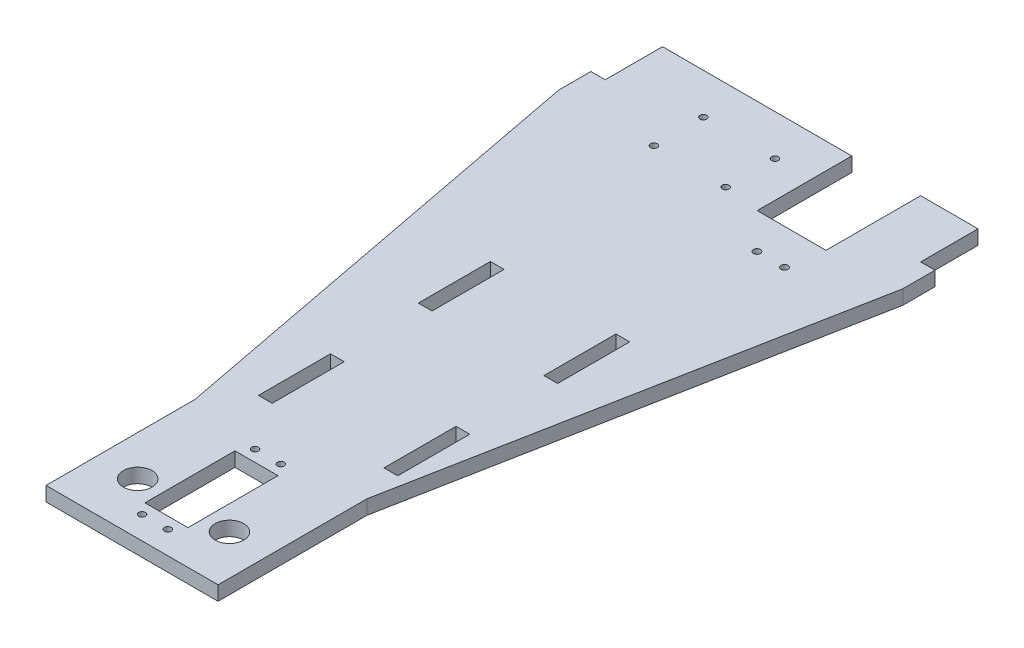
SolidWorks part; units mm, degrees
ref_plane "Front Plane" through (0, 0, 0) normal (0, 0, 1) x (1, 0, 0)
ref_plane "Top Plane" through (0, 0, 0) normal (0, 1, 0) x (1, 0, 0)
ref_plane "Right Plane" through (0, 0, 0) normal (1, 0, 0) x (0, 0, -1)
sketch "Sketch1" plane through (0, 0, 0) normal (0, 1, 0) x (1, 0, 0)
  line L1 (-90.17, 72.4607) -> (-90.17, 32.8367)
  line L2 (-90.17, 32.8367) -> (-52.07, -166.3716)
  line L4 (0, 72.4607) -> (0, 30.5507)
  line L5 (0, 30.5507) -> (30.48, 30.5507)
  line L6 (-13.97, 181.0208) -> (-13.97, -390.4349) construction
  line L7 (62.23, 32.8367) -> (24.13, -166.3716)
  line L8 (62.23, 72.4607) -> (62.23, 32.8367)
  line L9 (30.48, 72.4607) -> (30.48, 30.5507)
  line L16 (-79.0859, -278.1489) -> (174.9141, -278.1489) construction
  line L17 (-79.0859, -278.1489) -> (-79.0859, 128.2511) construction
  line L18 (-79.0859, 128.2511) -> (174.9141, 128.2511) construction
  line L19 (174.9141, -278.1489) -> (174.9141, 128.2511) construction
  line L21 (-79.0859, -74.9489) -> (174.9141, -74.9489) construction
  line L23 (-90.17, 60.9037) -> (62.23, 60.9037) construction
  line L24 (-90.17, 72.4607) -> (62.23, 72.4607) construction
  line L25 (-90.17, 72.4607) -> (0, 72.4607)
  line L26 (30.48, 72.4607) -> (62.23, 72.4607)
  line L27 (24.13, -166.3716) -> (24.13, -232.3393)
  line L28 (-52.07, -166.3716) -> (-52.07, -232.3393)
  line L29 (-52.07, -232.3393) -> (24.13, -232.3393)
  circle A0 centre (15.621, 14.8199) radius 1.55
  circle A1 centre (27.813, 14.8199) radius 1.55
  point P11 (-13.97, -260.0253)
  point P15 (25.4, 30.5507)
  point P495 (47.9141, -74.9489)
  dimension "D2" = 152.4
  dimension "D3" = 41.91
  dimension "D4" = 38.1
  dimension "D5" = 38.1
  dimension "D6" = 254
  dimension "D7" = 406.4
  dimension "D8" = 11.557
  dimension "D9" = 30.48
  dimension "D12" = 31.75
  dimension "D13" = 39.624
extrude "Boss-Extrude1" add sketch "Sketch1" along normal blind 6.35
sketch "Sketch2" plane through (62.23, 0, 0) normal (1, 0, 0) x (0, 0, -1)
  line L0 (72.4607, 6.35) -> (72.4607, 0)
  line L1 (32.8367, 6.35) -> (32.8367, 0) construction
  line L3 (32.8367, 6.35) -> (72.4607, 6.35) construction
  circle A2 centre (57.4747, 6.35) radius 3.175
  dimension "D1" = 24.638
sketch "Sketch4" plane through (0, 6.35, 0) normal (0, 1, 0) x (1, 0, 0)
  line L0 (-13.97, 30.5507) -> (-13.97, -232.3393) construction
  line L3 (-71.12, -199.3554) -> (43.18, -199.3554) construction
  line L7 (44.45, -212.0554) -> (-78.455, -212.0554) construction
  line L8 (62.23, 72.4607) -> (55.88, 72.4607)
  line L9 (62.23, 72.4607) -> (62.23, 47.0607)
  line L10 (62.23, 47.0607) -> (55.88, 47.0607)
  line L11 (55.88, 72.4607) -> (55.88, 47.0607)
  line L12 (59.055, 47.0607) -> (59.055, 72.4607) construction
  line L13 (62.23, 59.7607) -> (55.88, 59.7607) construction
  line L14 (-90.17, 72.4607) -> (-83.82, 72.4607)
  line L15 (-90.17, 72.4607) -> (-90.17, 47.0607)
  line L16 (-90.17, 47.0607) -> (-83.82, 47.0607)
  line L17 (-83.82, 72.4607) -> (-83.82, 47.0607)
  line L18 (-86.995, 47.0607) -> (-86.995, 72.4607) construction
  line L19 (-90.17, 59.7607) -> (-83.82, 59.7607) construction
  circle A0 centre (-34.29, -209.5154) radius 6.35
  circle A1 centre (6.35, -209.5154) radius 6.35
  point P346 (-86.995, 59.7607)
  point P378 (59.055, 59.7607)
  dimension "D5" = 12.7
  dimension "D2" = 10.16
  dimension "D8" = 12.7
  dimension "D1" = 10.16
  dimension "D4" = 12.7
  dimension "D9" = 6.35
  dimension "D10" = 25.4
  dimension "D11" = 6.35
  dimension "D12" = 25.4
  dimension "D13" = 20.32
  dimension "D14" = 20.32
extrude "Cut-Extrude2" cut sketch "Sketch4" against normal through all
sketch "Sketch5" plane through (0, 6.35, 0) normal (0, 1, 0) x (1, 0, 0)
  line L1 (-23.495, -177.2213) -> (-4.445, -177.2213)
  line L2 (-23.495, -177.2213) -> (-23.495, -217.0993)
  line L3 (-23.495, -217.0993) -> (-4.445, -217.0993)
  line L4 (-4.445, -177.2213) -> (-4.445, -217.0993)
  line L5 (55.88, 72.4607) -> (30.48, 72.4607) construction
  line L7 (0, 30.5507) -> (0, 72.4607) construction
  circle A0 centre (-19.685, -222.1793) radius 1.5
  circle A1 centre (-8.255, -222.1793) radius 1.5
  circle A2 centre (-19.685, -172.1413) radius 1.5
  circle A3 centre (-8.255, -172.1413) radius 1.5
  circle A4 centre (-16.002, 54.4267) radius 1.5
  circle A5 centre (-47.752, 54.4267) radius 1.5
  circle A6 centre (-47.752, 32.5827) radius 1.5
  circle A8 centre (-16.002, 32.5827) radius 1.5
  dimension "D5" = 3
  dimension "D10" = 3
  dimension "D11" = 3
  dimension "D16" = 3
  dimension "D19" = 3
  dimension "D22" = 3
  dimension "D23" = 3
  dimension "D27" = 3
  dimension "D1" = 19.05
  dimension "D2" = 39.878
  dimension "D6" = 5.08
  dimension "D7" = 3.81
  dimension "D8" = 5.08
  dimension "D9" = 3.81
  dimension "D12" = 5.08
  dimension "D13" = 5.08
  dimension "D14" = 3.81
  dimension "D15" = 3.81
  dimension "D17" = 18.034
  dimension "D20" = 18.034
  dimension "D24" = 47.752
  dimension "D25" = 39.878
  dimension "D26" = 39.878
  dimension "D28" = 16.002
extrude "Cut-Extrude3" cut sketch "Sketch5" against normal through all
sketch "Sketch9" plane through (0, 0, 0) normal (0, 1, 0) x (1, 0, 0)
  line L0 (16.0495, -118.8583) -> (22.127, -118.8583)
  line L1 (16.0495, -48.0464) -> (22.127, -48.0464)
  line L2 (16.0495, -48.0464) -> (16.0495, -79.9527)
  line L3 (16.0495, -79.9527) -> (22.127, -79.9527)
  line L4 (22.127, -48.0464) -> (22.127, -79.9527)
  line L5 (16.0495, -118.8583) -> (16.0495, -150.7646)
  line L6 (16.0495, -150.7646) -> (22.127, -150.7646)
  line L7 (22.127, -118.8583) -> (22.127, -150.7646)
  line L8 (-39.5607, -118.8583) -> (-33.4833, -118.8583)
  line L9 (-39.5607, -48.0464) -> (-33.4833, -48.0464)
  line L10 (-39.5607, -48.0464) -> (-39.5607, -79.9527)
  line L11 (-39.5607, -79.9527) -> (-33.4833, -79.9527)
  line L12 (-33.4833, -48.0464) -> (-33.4833, -79.9527)
  line L13 (-39.5607, -118.8583) -> (-39.5607, -150.7646)
  line L14 (-39.5607, -150.7646) -> (-33.4833, -150.7646)
  line L15 (-33.4833, -118.8583) -> (-33.4833, -150.7646)
extrude "Cut-Extrude4" cut sketch "Sketch9" along normal blind 37.338
